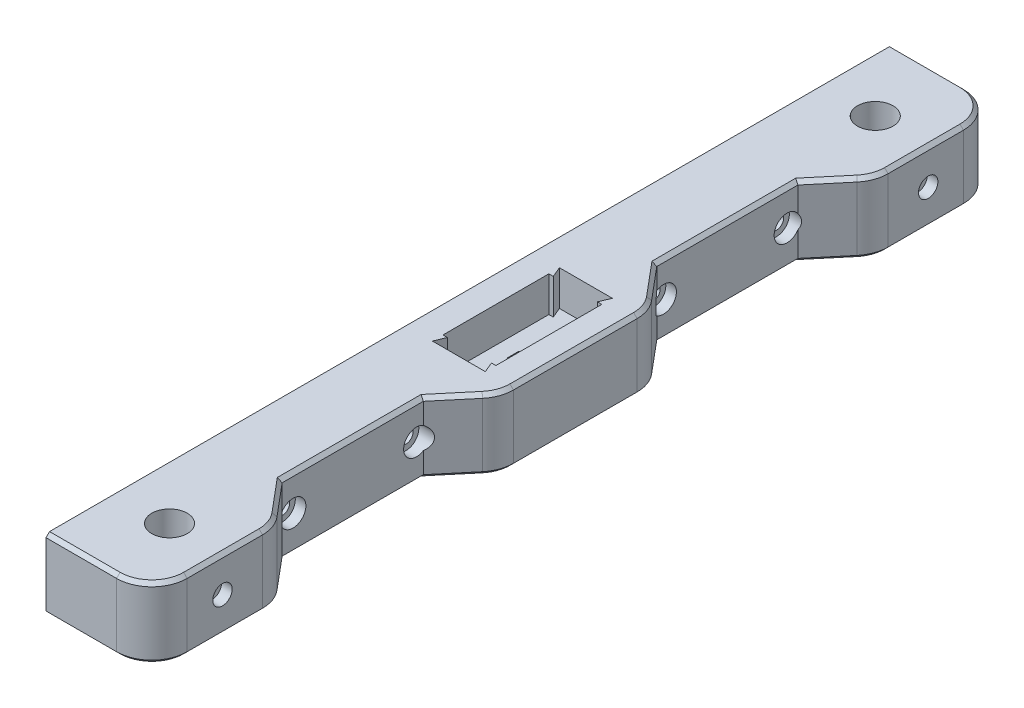
SolidWorks part; units mm, degrees
ref_plane "Front Plane" through (0, 0, 0) normal (0, 0, 1) x (1, 0, 0)
ref_plane "Top Plane" through (0, 0, 0) normal (0, 1, 0) x (1, 0, 0)
ref_plane "Right Plane" through (0, 0, 0) normal (1, 0, 0) x (0, 0, -1)
sketch "Sketch1" plane through (0, 0, 0) normal (1, 0, 0) x (0, 0, -1)
  line L1 (167.5998, 14.5216) -> (-72.4002, 14.5216)
  line L2 (167.5998, 14.5216) -> (167.5998, -5.4784)
  line L3 (167.5998, -5.4784) -> (-72.4002, -5.4784)
  line L4 (-72.4002, 14.5216) -> (-72.4002, -5.4784)
  dimension "D1" = 20
  dimension "D2" = 240
extrude "Boss-Extrude1" add sketch "Sketch1" along normal blind 30
sketch "Sketch2" plane through (0, 14.5216, 0) normal (0, 1, 0) x (1, 0, 0)
  line L0 (30, -72.4002) -> (0, -72.4002) construction
  line L1 (30, 167.5998) -> (0, 167.5998) construction
  line L2 (0, 167.5998) -> (0, -72.4002) construction
  circle A0 centre (15, 147.5998) radius 5.025
  circle A1 centre (15, -52.4002) radius 5.025
  dimension "D1" = 10.05
  dimension "D2" = 10.05
  dimension "D4" = 20
  dimension "D3" = 20
  dimension "D5" = 15
  dimension "D6" = 15
  dimension "D7" = 200
extrude "Cut-Extrude1" cut sketch "Sketch2" against normal blind 20
sketch "Sketch3" plane through (30, 0, 0) normal (1, 0, 0) x (0, 0, -1)
  line L0 (-72.4002, 14.5216) -> (-72.4002, -5.4784) construction
  line L1 (167.5998, -5.4784) -> (167.5998, 14.5216) construction
  line L2 (167.5998, 14.5216) -> (-72.4002, 14.5216) construction
  circle A0 centre (117.5998, 4.5216) radius 2.05
  circle A2 centre (-22.4002, 4.5216) radius 2.05
  circle A3 centre (12.5998, 4.5216) radius 2.05
  circle A4 centre (82.5998, 4.5216) radius 2.05
  dimension "D1" = 50
  dimension "D2" = 50
  dimension "D3" = 4.1
  dimension "D4" = 4.1
  dimension "D9" = 4.1
  dimension "D10" = 4.1
  dimension "D12" = 10
  dimension "D5" = 10
  dimension "D6" = 10
  dimension "D7" = 35
  dimension "D8" = 35
  dimension "D11" = 10
extrude "Cut-Extrude2" cut sketch "Sketch3" against normal blind 30
sketch "Sketch4" plane through (0, 14.5216, 0) normal (0, 1, 0) x (1, 0, 0)
  line L0 (0, 167.5998) -> (0, -72.4002) construction
  line L1 (22.5, 62.5998) -> (7.5, 62.5998)
  line L2 (22.5, 62.5998) -> (22.5, 32.5998)
  line L3 (22.5, 32.5998) -> (7.5, 32.5998)
  line L4 (7.5, 62.5998) -> (7.5, 32.5998)
  line L5 (30, -72.4002) -> (0, -72.4002) construction
  line L6 (30, 167.5998) -> (0, 167.5998) construction
  point P4 (22.5, 47.5998)
  dimension "D1" = 15
  dimension "D2" = 7.5
  dimension "D3" = 30
  dimension "D4" = 105
  dimension "D5" = 105
extrude "Cut-Extrude3" cut sketch "Sketch4" against normal blind 10
sketch "Sketch5" plane through (0, 4.5216, 0) normal (0, 1, 0) x (1, 0, 0)
  line L0 (22.5, 32.5998) -> (22.5, 62.5998) construction
  line L1 (15, 44.4243) -> (17.75, 46.0121)
  line L2 (17.75, 46.0121) -> (17.75, 49.1875)
  line L3 (17.75, 49.1875) -> (15, 50.7752)
  line L4 (15, 50.7752) -> (12.25, 49.1875)
  line L5 (12.25, 49.1875) -> (12.25, 46.0121)
  line L6 (12.25, 46.0121) -> (15, 44.4243)
  line L8 (7.5, 62.5998) -> (7.5, 32.5998) construction
  line L9 (22.5, 62.5998) -> (7.5, 62.5998) construction
  line L10 (7.5, 32.5998) -> (22.5, 32.5998) construction
  circle A0 centre (15, 47.5998) radius 2.75 construction
  point P1 (0, 0)
  point P11 (0, 0)
  point P13 (8.8366, 63.5467)
  dimension "D1" = 5.5
  dimension "D2" = 6.3509
  dimension "D3" = 7.5
  dimension "D4" = 7.5
  dimension "D5" = 15
  dimension "D6" = 15
extrude "Cut-Extrude4" cut sketch "Sketch5" against normal blind 2.5
sketch "Sketch6" plane through (0, -5.4784, 0) normal (0, -1, 0) x (1, 0, 0)
  line L0 (30, 37.4002) -> (20, 25.4827)
  line L1 (30, 72.4002) -> (30, -167.5998) construction
  line L2 (20, 25.4827) -> (20, -14.5173)
  line L3 (0, 72.4002) -> (0, -167.5998) construction
  line L4 (20, -14.5173) -> (30, -26.4348)
  line L5 (30, -68.7647) -> (20, -80.6822)
  line L6 (20, -80.6822) -> (20, -120.6822)
  line L7 (20, -120.6822) -> (30, -132.5998)
  line L8 (30, -167.5998) -> (0, -167.5998) construction
  line L9 (30, -132.5998) -> (30, -68.7647)
  line L10 (30, -26.4348) -> (30, 37.4002)
  dimension "D1" = 140
  dimension "D2" = 140
  dimension "D3" = 20
  dimension "D4" = 11.9175
  dimension "D5" = 11.9175
  dimension "D6" = 40
  dimension "D7" = 35
  dimension "D8" = 140
  dimension "D9" = 140
  dimension "D10" = 20
  dimension "D11" = 11.9175
  dimension "D12" = 11.9175
  dimension "D13" = 35
  dimension "D14" = 40
extrude "Cut-Extrude5" cut sketch "Sketch6" against normal blind 32.5
fillet "Fillet1" radius 10 2 edges at (30, 4.5216, -26.4348) (30, 4.5216, -68.7647)
fillet "Fillet2" radius 10 4 edges at (30, 4.5216, 72.4002) (30, 4.5216, -167.5998) (30, 4.5216, -132.5998) (30, 4.5216, 37.4002)
chamfer "Chamfer1" distance 1 angle 45 17 edges at (10, -5.4784, 72.4002) (23.8302, -5.4784, 30.0474) (27.0711, -5.4784, 69.4713) (29.3969, -5.4784, 37.6197) (30, -5.4784, 51.7201) (10, -5.4784, -167.5998) (27.0711, -5.4784, -164.6708) (30, -5.4784, -146.9196) (23.8302, -5.4784, -125.2469) (29.3969, -5.4784, -132.8193) (20, -5.4784, -100.6822) (23.8302, -5.4784, -76.1175) (29.3969, -5.4784, -68.5452) (30, -5.4784, -47.5998) (29.3969, -5.4784, -26.6543) (23.8302, -5.4784, -19.082) (20, -5.4784, 5.4827)
chamfer "Chamfer2" distance 1 angle 45 17 edges at (20, 14.5216, -100.6822) (10, 14.5216, -167.5998) (23.8302, 14.5216, -125.2469) (27.0711, 14.5216, -164.6708) (29.3969, 14.5216, -132.8193) (30, 14.5216, -146.9196) (23.8302, 14.5216, 30.0474) (10, 14.5216, 72.4002) (29.3969, 14.5216, 37.6197) (27.0711, 14.5216, 69.4713) (30, 14.5216, 51.7201) (20, 14.5216, 5.4827) (23.8302, 14.5216, -76.1175) (23.8302, 14.5216, -19.082) (29.3969, 14.5216, -68.5452) (29.3969, 14.5216, -26.6543) (30, 14.5216, -47.5998)
sketch "Sketch7" plane through (0, 2.0216, 0) normal (0, 1, 0) x (1, 0, 0)
  line L0 (12.25, 46.0121) -> (17.75, 49.1875) construction
  line L6 (12.25, 46.0121) -> (15, 44.4243)
  line L7 (15, 44.4243) -> (17.75, 46.0121)
  line L8 (17.75, 46.0121) -> (17.75, 49.1875)
  line L9 (17.75, 49.1875) -> (15, 50.7752)
  line L10 (15, 50.7752) -> (12.25, 49.1875)
  line L11 (12.25, 49.1875) -> (12.25, 46.0121)
  line L12 (12.25, 46.0121) -> (15, 44.4243) construction
  line L13 (15, 44.4243) -> (17.75, 46.0121) construction
  line L14 (17.75, 46.0121) -> (17.75, 49.1875) construction
  line L15 (17.75, 49.1875) -> (15, 50.7752) construction
  line L16 (15, 50.7752) -> (12.25, 49.1875) construction
  line L17 (12.25, 49.1875) -> (12.25, 46.0121) construction
  circle A0 centre (15, 47.5998) radius 1.6
  dimension "D2" = 3.2
  dimension "D1" = 0
extrude "Cut-Extrude6" cut sketch "Sketch7" against normal blind 32.5
sketch "Sketch8" plane through (0, 14.5216, 0) normal (0, 1, 0) x (1, 0, 0)
  line L0 (7.5, 65.5998) -> (8.75, 62.5998)
  line L1 (21.25, 62.5998) -> (8.75, 62.5998)
  line L3 (22.5, 65.5998) -> (7.5, 65.5998)
  line L4 (22.5, 32.5998) -> (22.5, 62.5998)
  line L5 (22.5, 62.5998) -> (7.5, 62.5998)
  line L6 (7.5, 62.5998) -> (7.5, 32.5998)
  line L7 (7.5, 32.5998) -> (22.5, 32.5998)
  line L9 (22.5, 62.5998) -> (7.5, 62.5998)
  line L11 (7.5, 32.5998) -> (22.5, 32.5998)
  line L13 (21.25, 32.5998) -> (8.75, 32.5998)
  line L15 (22.5, 29.5998) -> (7.5, 29.5998)
  line L17 (22.5, 65.5998) -> (21.25, 62.5998)
  line L18 (8.75, 32.5998) -> (7.5, 29.5998)
  line L19 (21.25, 32.5998) -> (22.5, 29.5998)
  point P2 (0, 0)
  point P4 (8.8425, 32.5998)
  point P6 (21.1642, 32.5998)
  dimension "D6" = 3
  dimension "D7" = 3
  dimension "D1" = 0
extrude "Cut-Extrude7" cut sketch "Sketch8" against normal blind 10 contours L3 L0 L1 L17 | L15 L18 L13 L19
sketch "Sketch9" plane through (0, -5.4784, 0) normal (0, -1, 0) x (1, 0, 0)
  circle A0 centre (15, -47.5998) radius 3
  dimension "D1" = 6
extrude "Cut-Extrude8" cut sketch "Sketch9" against normal blind 3
fillet "Fillet3" radius 1 1 edges at (15, -5.4784, -50.5998)
sketch "Sketch10" plane through (20, 0, 0) normal (1, 0, 0) x (0, 0, -1)
  line L15 (120.6822, -4.4784) -> (120.6822, 13.5216)
  line L16 (120.6822, 13.5216) -> (80.6822, 13.5216)
  line L17 (80.6822, 13.5216) -> (80.6822, 5.2466)
  line L18 (80.6822, 3.7967) -> (80.6822, -4.4784)
  line L19 (80.6822, -4.4784) -> (120.6822, -4.4784)
  line L21 (120.6822, 13.5216) -> (80.6822, 13.5216)
  line L24 (80.6822, -4.4784) -> (120.6822, -4.4784)
  circle A0 centre (12.5998, 4.5216) radius 3.65
  arc A3 (80.6822, 3.7967) -> (80.6822, 5.2466) centre (82.5998, 4.5216) ccw
  circle A5 centre (-22.4002, 4.5216) radius 3.65
  circle A6 centre (82.5998, 4.5216) radius 3.65
  circle A7 centre (117.5998, 4.5216) radius 3.65
  dimension "D3" = 7.3
  dimension "D4" = 7.3
  dimension "D5" = 7.3
  dimension "D6" = 7.3
  dimension "D2" = 0
extrude "Cut-Extrude9" cut sketch "Sketch10" against normal blind 3 and the other way blind 3 contours A7 | A6 | A0 | A5
sketch "Sketch11" plane through (30, 0, 0) normal (1, 0, 0) x (0, 0, -1)
  line L0 (136.2395, 14.5216) -> (157.5998, 14.5216) construction
  line L1 (-62.4002, 14.5216) -> (-41.0399, 14.5216) construction
  line L2 (167.5998, 13.5216) -> (167.5998, -4.4784) construction
  line L3 (-72.4002, -4.4784) -> (-72.4002, 13.5216) construction
  circle A0 centre (147.5998, 4.5216) radius 1.5
  circle A1 centre (-52.4002, 4.5216) radius 1.5
  point P4 (0, 0)
  dimension "D1" = 3
  dimension "D2" = 3
  dimension "D3" = 10
  dimension "D4" = 10
  dimension "D5" = 20
  dimension "D6" = 20
extrude "Cut-Extrude10" cut sketch "Sketch11" against normal blind 13
sketch "Sketch12" plane through (30, 0, 0) normal (1, 0, 0) x (0, 0, -1)
  circle A0 centre (147.5998, 4.5216) radius 1.5 construction
  circle A1 centre (147.5998, 4.5216) radius 1.5
  circle A2 centre (-52.4002, 4.5216) radius 1.5 construction
  circle A3 centre (-52.4002, 4.5216) radius 1.5
  circle A4 centre (-52.4002, 4.5216) radius 2.75
  circle A5 centre (147.5998, 4.5216) radius 2.75
  dimension "D1" = 5.5
  dimension "D2" = 5.5
extrude "Cut-Extrude11" cut sketch "Sketch12" against normal blind 3
